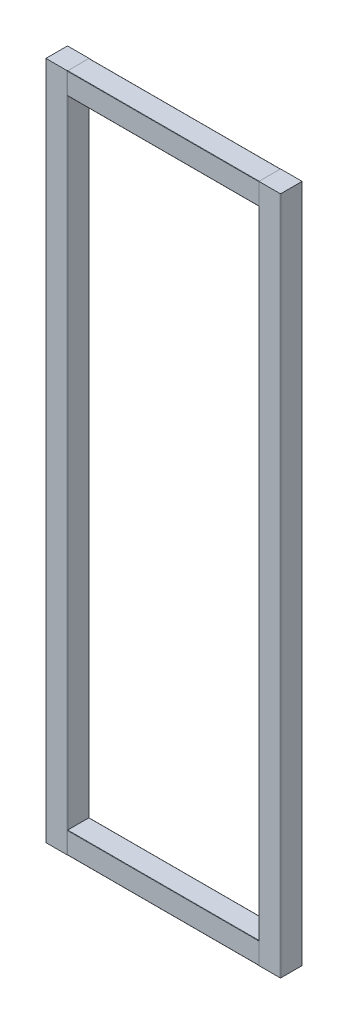
SolidWorks part; units mm, degrees
material "Pin"
ref_plane "Plan de face" through (0, 0, 0) normal (0, 0, 1) x (1, 0, 0)
ref_plane "Plan de dessus" through (0, 0, 0) normal (0, 1, 0) x (1, 0, 0)
ref_plane "Plan de droite" through (0, 0, 0) normal (1, 0, 0) x (0, 0, -1)
sketch "Esquisse1" plane through (0, 0, 0) normal (0, 0, 1) x (1, 0, 0)
  line L1 (172.5, -532.5) -> (-172.5, -532.5)
  line L2 (172.5, -532.5) -> (172.5, 532.5)
  line L3 (172.5, 532.5) -> (-172.5, 532.5)
  line L4 (-172.5, -532.5) -> (-172.5, 532.5)
  line L5 (172.5, -532.5) -> (-172.5, 532.5) construction
  line L6 (172.5, 532.5) -> (-172.5, -532.5) construction
  point P0 (0, 0)
  dimension "D1" = 345
  dimension "D2" = 1065
other "Custom TASSEAU-CARRE-33(1)"
ref_plane "Plan1" through (172.5, -532.5, 0) normal (0, 1, 0) x (-1, 0, 0)
sketch "Esquisse14" plane through (172.5, -532.5, 0) normal (0, 1, 0) x (-1, 0, 0)
  line L5 (-15, -15) -> (15, 15) construction
  line L6 (-15, 15) -> (15, -15) construction
  line L7 (-17, -17.5) -> (17, -17.5)
  line L8 (-17.5, -17) -> (-17.5, 17)
  line L9 (-17, 17.5) -> (17, 17.5)
  line L10 (17.5, -17) -> (17.5, 17)
  line L11 (-17.5, -17.5) -> (17.5, 17.5) construction
  line L12 (-17.5, 17.5) -> (17.5, -17.5) construction
  arc A0 (17, -17.5) -> (17.5, -17) centre (17, -17) ccw
  arc A3 (-17, -17.5) -> (-17.5, -17) centre (-17, -17) cw
  arc A4 (17, 17.5) -> (17.5, 17) centre (17, 17) cw
  arc A7 (-17.5, 17) -> (-17, 17.5) centre (-17, 17) cw
  point P0 (0, 0)
  point P6 (0, 0)
  point P14 (0, 0)
  point P35 (0, 17.5)
  point P36 (0, 15)
  point P37 (-15, 0)
  point P38 (-17.5, 0)
  point P39 (0, -15)
  point P40 (0, -17.5)
  point P41 (15, 0)
  point P42 (17.5, 0)
  dimension "D5" = 0.5
  dimension "D1" = 0.5
  dimension "D4" = 0.5
  dimension "D2" = 35
  dimension "D3" = 35
